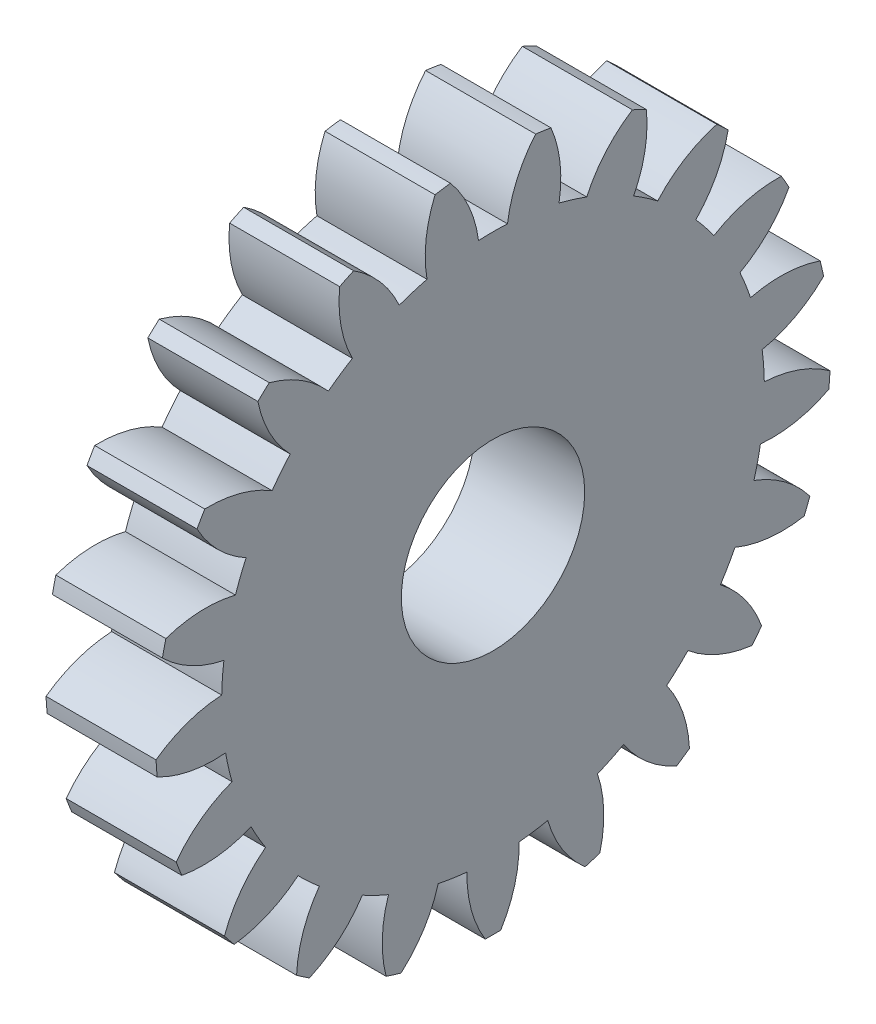
SolidWorks part; units mm, degrees
ref_plane "Plane1" through (0, 0, 0) normal (0, 0, 1) x (1, 0, 0)
ref_plane "Plane2" through (0, 0, 0) normal (0, 1, 0) x (1, 0, 0)
ref_plane "Plane3" through (0, 0, 0) normal (1, 0, 0) x (0, 0, -1)
sketch "HoldingSke" plane through (0, 0, 0) normal (0, 1, 0) x (1, 0, 0)
  line L0 (0, 0) -> (1.167, -0.448)
  line L1 (-15, 0) -> (100, 0) construction
  line L2 (0, 0) -> (-2.1039, 2.3779)
  line L3 (0, 0) -> (-11.863, 4.5341)
  line L4 (0, 0) -> (8.0624, 3.0949)
  line L5 (0, 0) -> (-46.8476, -17.4728)
  line L6 (0, 0) -> (-9.9476, -6.7116)
  line L7 (-2.1039, 2.3779) -> (8.6586, 51.2059)
  line L8 (-76.2, 54.61) -> (-75.3, 54.61)
  line L9 (-71.009, 38.7566) -> (-53.1078, 45.2721)
  line L10 (-76.2, 71.12) -> (104.1128, 71.12)
  line L11 (0, 0) -> (-12, 0)
  line L12 (-76.2, 101.6) -> (-76.17, 101.6)
  line L13 (24.9733, 27.94) -> (52.9518, 28.4284)
  line L14 (24.9733, 27.94) -> (24.9743, 27.94)
  line L15 (24.9733, 27.94) -> (100.4006, 29.5858)
  line L16 (-63.627, -0.8) -> (-12.827, -0.8)
  circle A0 centre (0, 0) radius 2.5
  circle A1 centre (0, 0) radius 7.399
  circle A2 centre (0, 0) radius 37.5
  circle A3 centre (0, 0) radius 2.5
  dimension "MHD" = 14.798
  dimension "Hub_dia" = 75
  dimension "Bore" = 5
  dimension "MBD" = 5
  dimension "Num_teeth" = 21
  dimension "Pitch" = 1.25
  dimension "Overall_len" = 50
  dimension "Show_teeth" = 21
  dimension "Thickness" = 12
  dimension "OAL" = 50.0001
  dimension "T_dim" = 0.9
  dimension "Ap" = 20
  dimension "H" = 19.05
  dimension "Pitch_radius" = 180.3128
  dimension "Width" = 12
  dimension "Backlash" = 0.03
  dimension "Addendum_fac" = 1
  dimension "Dedendum_fac" = 1.25
  dimension "Clearance_fac" = 0.25
  dimension "Dedendum_add" = 0.001
  dimension "Module" = 0.8
sketch "BasProSke" plane through (0, 0, 0) normal (0, 1, 0) x (1, 0, 0)
  line L0 (-10, 0) -> (60, 0) construction
  line L1 (0, 0) -> (0, 9.2)
  line L2 (0, 0) -> (12, 0)
  line L3 (12, 0) -> (12, 9.2)
  line L4 (12, 9.2) -> (0, 9.2)
  dimension "Thickness" = 12
  dimension "Diameter" = 18.4
revolve "Base-Revolve" add sketch "BasProSke" angle 360 about L0
sketch "TooCutSke" plane through (0, 0, 0) normal (1, 0, 0) x (0, 0, -1)
  line L1 (0, 0) -> (0, 107) construction
  line L2 (0, 0) -> (-0.6802, 8.3724) construction
  line L3 (0, 0) -> (-2.498, 16.5734) construction
  line L4 (-0.6802, 8.3724) -> (-1.249, 8.2867) construction
  arc A0 (0.3956, 7.3884) -> (-0.3956, 7.3884) centre (0, 0) ccw
  arc A1 (1.1812, 9.1495) -> (-1.1812, 9.1495) centre (0, 0) ccw
  circle A2 centre (0, 0) radius 8.4 construction
  circle A3 centre (0, 0) radius 7.8934 construction
  arc A4 (-0.3956, 7.3884) -> (-1.1812, 9.1495) centre (-3.7278, 6.9577) ccw
  arc A5 (1.1812, 9.1495) -> (0.3956, 7.3884) centre (3.7278, 6.9577) ccw
  dimension "Root_dia" = 14.798
  dimension "Overcut_dia" = 18.4508
  dimension "Pitch_dia" = 16.8
  dimension "Base_dia" = 15.7868
  dimension "Flank_rad" = 3.36
  dimension "Half_ang" = 8.571
  dimension "Half_CT" = 0.5752
extrude "ToothCut" cut sketch "TooCutSke" along normal through all
fillet "Breaks" [suppressed] radius 0.016
fillet "RootFillets" [suppressed] radius 0.201
pattern_circular "TeethCuts" count 21 every 17.143 about axis through (-10, 0, 0) along (1, 0, 0) of "ToothCut", "RootFillets", "Breaks"
sketch "HubNeaOneSke" plane through (0, 0, 0) normal (-1, 0, 0) x (0, 0, 1)
  circle A0 centre (0, 0) radius 7.399
  dimension "Diameter" = 14.798
extrude "HubNearOne" [suppressed] add sketch "HubNeaOneSke" along normal blind 38.0001
sketch "HubNeaBotSke" plane through (0, 0, 0) normal (-1, 0, 0) x (0, 0, 1)
  circle A0 centre (0, 0) radius 7.399
  dimension "Diameter" = 14.798
extrude "HubNearBoth" [suppressed] add sketch "HubNeaBotSke" along normal blind 19
ref_plane "FarPln" through (12, 0, 0) normal (1, 0, 0) x (0, 0, -1)
sketch "HubFarSke" plane through (12, 0, 0) normal (1, 0, 0) x (0, 0, -1)
  circle A0 centre (0, 0) radius 7.399
  dimension "Diameter" = 14.798
extrude "HubFar" [suppressed] add sketch "HubFarSke" along normal blind 19
sketch "BorSke" plane through (0, 0, 0) normal (1, 0, 0) x (0, 0, -1)
  circle A0 centre (0, 0) radius 2.5
  dimension "Diameter" = 5
extrude "Bore" cut sketch "BorSke" along normal mid plane 100.0001
sketch "KeySke" plane through (0, 0, 0) normal (1, 0, 0) x (0, 0, -1)
  line L0 (-1, 0) -> (-1, 3.4)
  line L1 (-1, 3.4) -> (1, 3.4)
  line L2 (1, 3.4) -> (1, 0)
  line L3 (0, 0) -> (0, 34) construction
  line L4 (-1, 0) -> (1, 0)
  dimension "Offset" = 3.4
  dimension "Width" = 2
extrude "Keyway" [suppressed] cut sketch "KeySke" along normal mid plane 100.0001
pattern_circular "Keyway2" [suppressed] count 2 every 90 about axis through (-10, 0, 0) along (1, 0, 0)
sketch "Croquis1" plane through (12, 0, 0) normal (1, 0, 0) x (0, 0, -1)
  line L1 (-9.8863, 10.1607) -> (9.8863, 10.1607)
  line L2 (-9.8863, 10.1607) -> (-9.8863, -9.76)
  line L3 (-9.8863, -9.76) -> (9.8863, -9.76)
  line L4 (9.8863, 10.1607) -> (9.8863, -9.76)
extrude "Cortar-Extruir1" cut sketch "Croquis1" against normal blind 9
equation "' \"Module@HoldingSke\" = 6.35"
equation "' \"Num_teeth@HoldingSke\" = 12"
equation "' \"Ap@HoldingSke\" =  20"
equation "' \"Ap@HoldingSke\" = 20"
equation "' \"Width@HoldingSke\" = 0.5 * 25.4"
equation "' \"Hub_dia@HoldingSke\"= 1 * 25.4"
equation "' \"Hub_dia@HoldingSke\" = 1 * 25.4"
equation "' \"Overall_len@HoldingSke\" = 1.0 * 25.4"
equation "' \"Bore@HoldingSke\" = 0.75 * 25.4"
equation "' \"T_dim@HoldingSke\" = 0.1 * 25.4"
equation "' \"Width@KeySke\" = 0.25 * 25.4"
equation "' \"Show_teeth@HoldingSke\" = 13"
equation "' \"Backlash@HoldingSke\" = 0.009 * 25.4"
equation "' \"Addendum_fac@HoldingSke\" = 1.0"
equation "' \"Dedendum_fac@HoldingSke\" = 1.25"
equation "' \"Dedendum_add@HoldingSke\" = 0.00005 * 25.4"
equation "' \"Clearance_fac@HoldingSke\" = 0.25"
equation "\"Pitch@HoldingSke\" = 1 / \"Module@HoldingSke\""
equation "\"Overcut_dia@TooCutSke\" = (\"Num_teeth@HoldingSke\" + 2 * \"Addendum_fac@HoldingSke\") / \"Pitch@HoldingSke\" + 0.002 * 25.4"
equation "\"Pitch_dia@TooCutSke\" = \"Num_teeth@HoldingSke\" / \"Pitch@HoldingSke\""
equation "\"Base_dia@TooCutSke\" = \"Num_teeth@HoldingSke\" / \"Pitch@HoldingSke\" * cos((\"Ap@HoldingSke\"  * 3.14159265 / 180))"
equation "\"Root_dia@TooCutSke\" = (\"Num_teeth@HoldingSke\" + 2) / \"Pitch@HoldingSke\" - 2 * (\"Addendum_fac@HoldingSke\" + \"Dedendum_fac@HoldingSke\") / \"Pitch@HoldingSke\" - \"Dedendum_add@HoldingSke\" * 2"
equation "\"Half_ang@TooCutSke\" = 180 / \"Num_teeth@HoldingSke\""
equation "\"Half_CT@TooCutSke\" = \"Num_teeth@HoldingSke\" / \"Pitch@HoldingSke\" * sin((3.14159265 / 2 / \"Num_teeth@HoldingSke\")) / 2 - 7 * \"Backlash@HoldingSke\" / 4"
equation "\"Flank_rad@TooCutSke\" = \"Num_teeth@HoldingSke\" / \"Pitch@HoldingSke\" / 5"
equation "\"Radius@RootFillets\" = \"Clearance_fac@HoldingSke\" / \"Pitch@HoldingSke\" + \"Dedendum_add@HoldingSke\""
equation "\"Break_rad@Breaks\" = 0.02 / \"Pitch@HoldingSke\""
equation "\"Thickness@HoldingSke\" = \"Width@HoldingSke\""
equation "\"OAL@HoldingSke\" = \"Thickness@HoldingSke\""
equation "\"MHD@HoldingSke\" = (\"Num_teeth@HoldingSke\" + 2) / \"Pitch@HoldingSke\" - 2 * (\"Addendum_fac@HoldingSke\" + \"Dedendum_fac@HoldingSke\")  / \"Pitch@HoldingSke\" - \"Dedendum_add@HoldingSke\" * 2"
equation "\"MBD@HoldingSke\" = (\"Num_teeth@HoldingSke\" + 2) / \"Pitch@HoldingSke\" - 2 * (\"Addendum_fac@HoldingSke\" + \"Dedendum_fac@HoldingSke\")  / \"Pitch@HoldingSke\" - \"Dedendum_add@HoldingSke\" * 2 - 0.002 * 25.4"
equation "\"MHD@HoldingSke\" = ((sgn( \"MHD@HoldingSke\" - \"Hub_dia@HoldingSke\" )-1)*( \"MHD@HoldingSke\" - \"Hub_dia@HoldingSke\" ))/-2+ \"Hub_dia@HoldingSke\""
equation "\"MBD@HoldingSke\" = ((sgn( \"MBD@HoldingSke\" - \"Bore@HoldingSke\" )-1)*( \"MBD@HoldingSke\" - \"Bore@HoldingSke\" ))/-2+ \"Bore@HoldingSke\""
equation "\"OAL@HoldingSke\" = ((sgn( \"OAL@HoldingSke\" - \"Overall_len@HoldingSke\" )+1)*( \"OAL@HoldingSke\" - \"Overall_len@HoldingSke\" ))/2 + \"Overall_len@HoldingSke\" + 0.000002 * 25.4"
equation "\"Num_teeth@TeethCuts\" = int( \"Show_teeth@HoldingSke\" ) + 1"
equation "\"Num_teeth@TeethCuts\" = ((sgn( \"Num_teeth@TeethCuts\" - \"Num_teeth@HoldingSke\" )-1)*( \"Num_teeth@TeethCuts\" - \"Num_teeth@HoldingSke\" ))/-2+ \"Num_teeth@HoldingSke\""
equation "\"Num_teeth@TeethCuts\" = ((sgn( \"Num_teeth@TeethCuts\" - 2.0)+1)*( \"Num_teeth@TeethCuts\" - 2.0))/2 +2.0"
equation "\"Angle@TeethCuts\" = 360.0 / \"Num_teeth@HoldingSke\""
equation "\"Diameter@BasProSke\" = (\"Num_teeth@HoldingSke\" + 2 * \"Addendum_fac@HoldingSke\") / \"Pitch@HoldingSke\""
equation "\"Thickness@BasProSke\"  = \"Thickness@HoldingSke\""
equation "' \"Fillet_rad@BasProSke\" =  \"Thickness@HoldingSke\" * 0.05"
equation "' \"Fillet_rad@BasProSke\" = \"Thickness@HoldingSke\" * 0.05"
equation "\"MHD@HoldingSke\" = ((sgn( \"MHD@HoldingSke\" - \"Root_dia@TooCutSke\" )-1)*( \"MHD@HoldingSke\" - \"Root_dia@TooCutSke\" ))/-2+ \"Root_dia@TooCutSke\""
equation "\"Diameter@HubNeaOneSke\" = \"MHD@HoldingSke\""
equation "\"Length@HubNearOne\" = \"OAL@HoldingSke\" - \"Thickness@BasProSke\""
equation "\"Diameter@HubNeaBotSke\" = \"MHD@HoldingSke\""
equation "\"Length@HubNearBoth\" = ( \"OAL@HoldingSke\" - \"Thickness@BasProSke\" ) / 2.0"
equation "\"Thickness@FarPln\" = \"Thickness@BasProSke\""
equation "\"Diameter@HubFarSke\" = \"MHD@HoldingSke\""
equation "\"Length@HubFar\" = ( \"OAL@HoldingSke\" - \"Thickness@BasProSke\" ) / 2.0"
equation "\"Diameter@BorSke\" = \"MBD@HoldingSke\""
equation "\"D1@Bore\" = \"OAL@HoldingSke\" * 2.0"
equation "\"D1@Keyway\" = \"OAL@HoldingSke\" * 2.0"
equation "\"Offset@KeySke\" = \"T_dim@HoldingSke\" + \"MBD@HoldingSke\" / 2.0"
